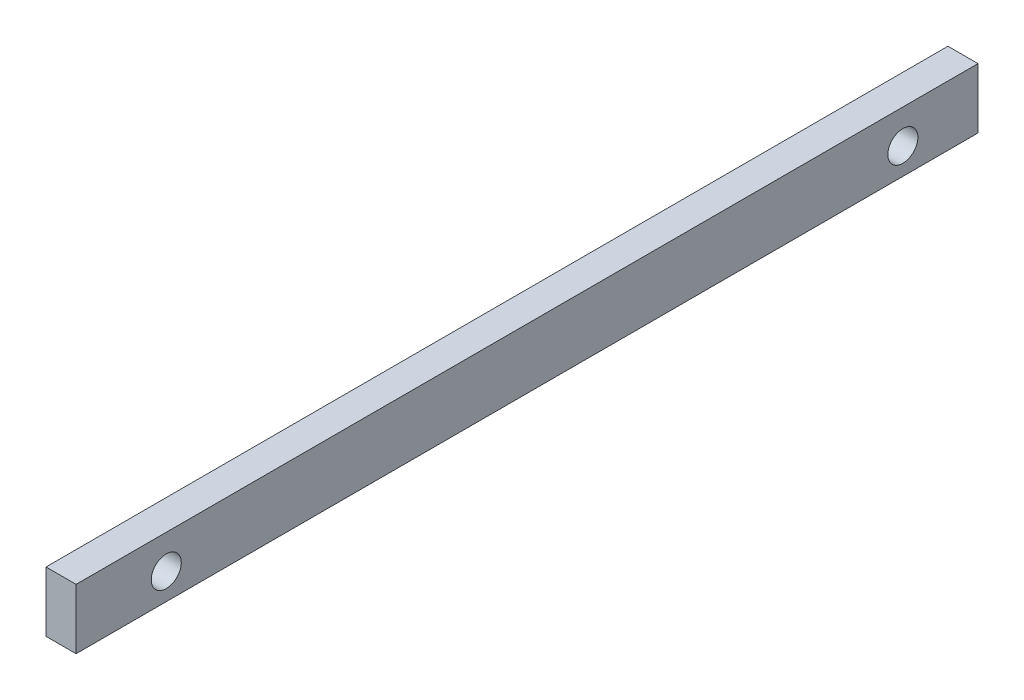
SolidWorks part; units mm, degrees
ref_plane "Front Plane" through (0, 0, 0) normal (0, 0, 1) x (1, 0, 0)
ref_plane "Top Plane" through (0, 0, 0) normal (0, 1, 0) x (1, 0, 0)
ref_plane "Right Plane" through (0, 0, 0) normal (1, 0, 0) x (0, 0, -1)
sketch "Sketch1" plane through (0, 0, 0) normal (1, 0, 0) x (0, 0, -1)
  line L1 (-40.1373, 5.316) -> (79.8627, 5.316)
  line L2 (-40.1373, 5.316) -> (-40.1373, -2.684)
  line L3 (-40.1373, -2.684) -> (79.8627, -2.684)
  line L4 (79.8627, 5.316) -> (79.8627, -2.684)
  circle A0 centre (-28.1373, 0.8275) radius 2
  circle A1 centre (69.8627, 0.8275) radius 2
  dimension "D3" = 100
  dimension "D1" = 120
  dimension "D2" = 8
  dimension "D4" = 10
extrude "Boss-Extrude1" add sketch "Sketch1" along normal blind 4
